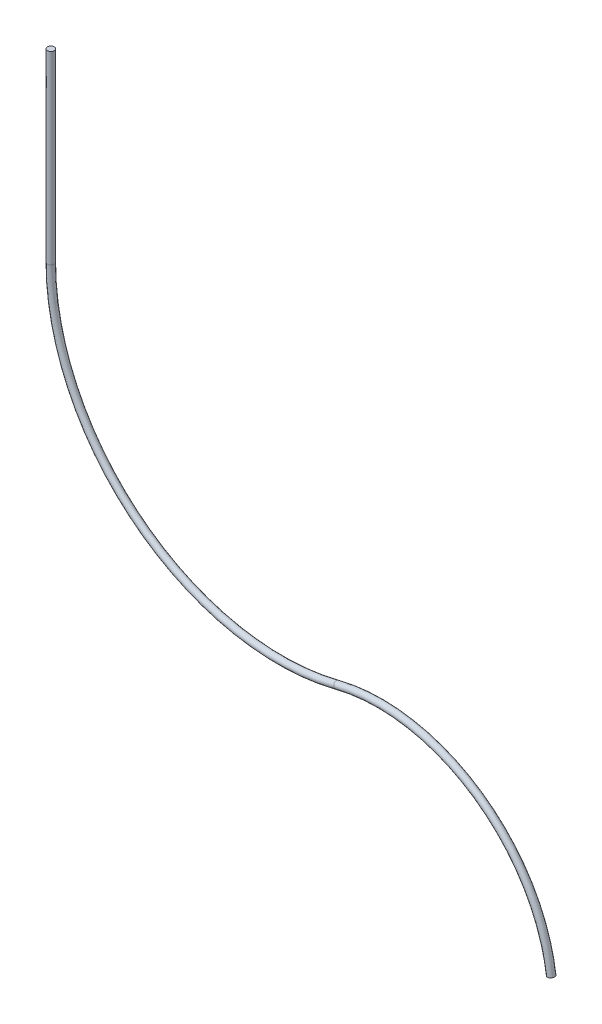
SolidWorks part; units mm, degrees
ref_plane "Front Plane" through (0, 0, 0) normal (0, 0, 1) x (1, 0, 0)
ref_plane "Top Plane" through (0, 0, 0) normal (0, 1, 0) x (1, 0, 0)
ref_plane "Right Plane" through (0, 0, 0) normal (1, 0, 0) x (0, 0, -1)
sketch "Sketch1" plane through (0, 0, 0) normal (0, 0, 1) x (1, 0, 0)
  line L0 (0, 0) -> (0, -218.9084)
  arc A0 (0, -218.9084) -> (339.1678, -482.6202) centre (272.1053, -218.9084) ccw
  arc A1 (339.1678, -482.6202) -> (592.4934, -654.1321) centre (389.6062, -680.9608) cw
sweep "Sweep1" add path "Sketch1" circular profile diameter 8 parameters "D3"=8
